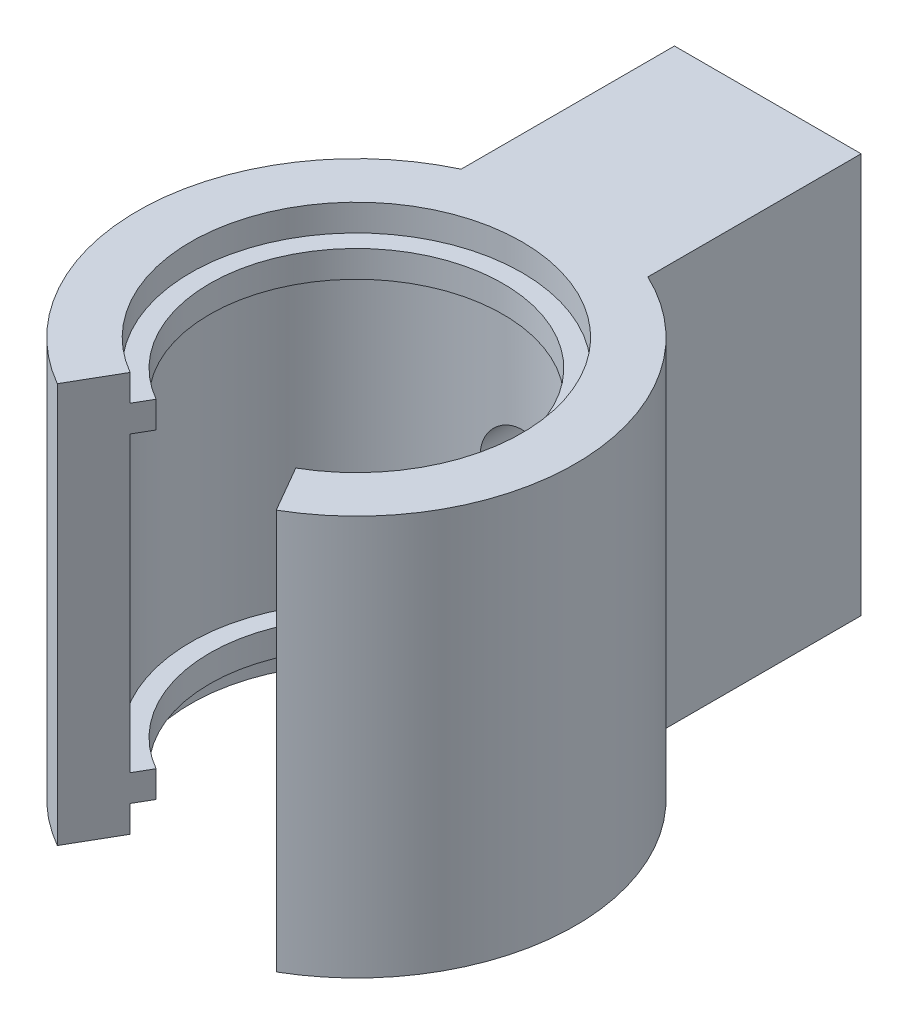
SolidWorks part; units mm, degrees
ref_plane "Front Plane" through (0, 0, 0) normal (0, 0, 1) x (1, 0, 0)
ref_plane "Top Plane" through (0, 0, 0) normal (0, 1, 0) x (1, 0, 0)
ref_plane "Right Plane" through (0, 0, 0) normal (1, 0, 0) x (0, 0, -1)
sketch "Sketch1" plane through (0, 0, 0) normal (0, 1, 0) x (1, 0, 0)
  line L0 (-3.5, 7.428) -> (3.5, 7.428) construction
  line L1 (-3.5, 7.428) -> (0, 0) construction
  line L2 (0, 0) -> (3.5, 7.428) construction
  line L3 (-3.5, 7.428) -> (-3.5, 15.428)
  line L4 (3.5, 7.428) -> (3.5, 15.428)
  line L5 (-3.5, 15.428) -> (3.5, 15.428)
  line L6 (0, 0) -> (0, 15.428) construction
  circle A0 centre (0, 0) radius 6.2113
  arc A1 (-3.5, 7.428) -> (3.5, 7.428) centre (0, 0) ccw
  dimension "D1" = 7
  dimension "D3" = 8
  dimension "D2" = 2
extrude "Boss-Extrude1" add sketch "Sketch1" along normal blind 15
sketch "Sketch2" plane through (0, 0, -15.428) normal (0, 0, -1) x (-1, 0, 0)
sketch "Sketch4" plane through (0, 15, 0) normal (0, 1, 0) x (1, 0, 0)
  line L0 (-3.1056, -5.3791) -> (-4.1056, -7.1112)
  line L1 (3.1056, -5.3791) -> (4.1056, -7.1112)
  line L2 (0, 0) -> (-4.1056, -7.1112) construction
  line L3 (0, 0) -> (4.1056, -7.1112) construction
  line L5 (-4.1056, -7.1112) -> (4.1056, -7.1112) construction
  circle A0 centre (0, 0) radius 6.2113 construction
  arc A1 (-3.5, 7.428) -> (3.5, 7.428) centre (0, 0) ccw construction
  arc A2 (-3.1056, -5.3791) -> (3.1056, -5.3791) centre (0, 0) ccw
  arc A3 (-4.1056, -7.1112) -> (4.1056, -7.1112) centre (0, 0) ccw
  dimension "D1" = 60
extrude "Cut-Extrude1" cut sketch "Sketch4" against normal through all both and the other way through all
ref_plane "Plane2" through (0, 1, 0) normal (0, -1, 0) x (-1, 0, 0)
sketch "Sketch5" plane through (0, 1, 0) normal (0, -1, 0) x (-1, 0, 0)
  line L0 (3.1056, -5.3791) -> (2.75, -4.7631)
  line L1 (-2.75, -4.7631) -> (-3.1056, -5.3791)
  line L2 (-4.1056, -7.1112) -> (-3.1056, -5.3791) construction
  arc A0 (2.75, -4.7631) -> (-2.75, -4.7631) centre (0, 0) ccw
  arc A1 (-3.1056, -5.3791) -> (3.1056, -5.3791) centre (0, 0) cw
extrude "Boss-Extrude3" add sketch "Sketch5" against normal blind 1
ref_plane "Plane3" through (0, 7.5, 0) normal (0, 1, 0) x (1, 0, 0)
mirror "Mirror1" about plane through (0, 7.5, 0) normal (0, 1, 0) of "Boss-Extrude3"
sketch "Sketch6" plane through (0, 0, -15.428) normal (0, 0, -1) x (-1, 0, 0)
  line L0 (8.8, 7.5) -> (-8.8, 7.5) construction
  line L1 (0, 15) -> (0, 0) construction
  line L2 (-3.5, 15) -> (3.5, 15) construction
  circle A0 centre (0, 7.5) radius 1.4
  dimension "D1" = 2.8
extrude "Cut-Extrude2" cut sketch "Sketch6" against normal blind 10 contours A0
